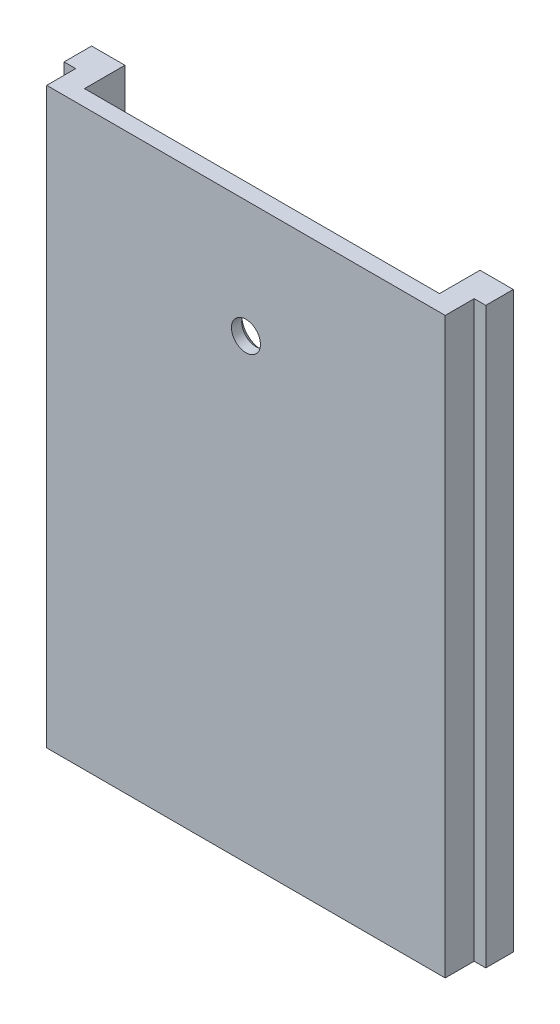
SolidWorks part; units mm, degrees
ref_plane "Alzado" through (0, 0, 0) normal (0, 0, 1) x (1, 0, 0)
ref_plane "Planta" through (0, 0, 0) normal (0, 1, 0) x (1, 0, 0)
ref_plane "Vista lateral" through (0, 0, 0) normal (1, 0, 0) x (0, 0, -1)
sketch "Croquis1" plane through (0, 0, 0) normal (0, 1, 0) x (1, 0, 0)
  line L5 (-4, 10) -> (-4, 19.5)
  line L14 (7.5, 19.5) -> (7.5, 5.5361)
  line L17 (-4, 19.5) -> (7.5, 19.5)
  line L19 (0, 0) -> (137.5, 0)
  line L20 (0, 0) -> (0, 10)
  line L21 (0, 10) -> (-4, 10)
  line L23 (7.5, 5.5361) -> (130, 5.5361)
  line L25 (68.75, 54.2093) -> (68.75, -41.2998) construction
  line L26 (137.5, 10) -> (141.5, 10)
  line L27 (137.5, 0) -> (137.5, 10)
  line L28 (141.5, 19.5) -> (130, 19.5)
  line L29 (130, 19.5) -> (130, 5.5361)
  line L30 (141.5, 10) -> (141.5, 19.5)
  point P3 (68.75, 5.5361)
  point P12 (68.75, 0)
  dimension "D1" = 68.75
  dimension "D2" = 10
  dimension "D3" = 9.5
  dimension "D4" = 11.5
  dimension "D5" = 72.75
  dimension "D7" = 5.5361
extrude "Saliente-Extruir4" add sketch "Croquis1" along normal blind 198 contours L17 L14 L23 L29 L28 L30 L26 L27 L19 L20 L21 L5
ref_plane "Plano1" through (68.75, 0, 0) normal (1, 0, 0) x (0, 0, -1)
sketch "Croquis2" plane through (0, 0, -5.5361) normal (0, 0, -1) x (-1, 0, 0)
  line L0 (-7.5, 0) -> (-130, 0) construction
  line L1 (-7.5, 0) -> (-130, 0) construction
  line L2 (-7.5, 198) -> (-7.5, 0) construction
  line L3 (-130, 198) -> (-130, 0) construction
  line L4 (-7.5, 198) -> (-7.5, 0) construction
  line L5 (-130, 198) -> (-130, 0) construction
  line L6 (-130, 108) -> (-7.5, 108)
  line L7 (-130, 105) -> (-7.5, 105)
  line L8 (-130, 108) -> (-130, 105)
  line L9 (-7.5, 108) -> (-7.5, 105)
  dimension "D1" = 108
  dimension "D2" = 3
extrude "Saliente-Extruir5" add sketch "Croquis2" along normal up to surface (13.9639 mm away) up to face at (135.75, 99, -19.5)
sketch "Croquis3" plane through (0, 0, 0) normal (0, 0, 1) x (1, 0, 0)
  line L0 (68.75, 198) -> (68.75, 0) construction
  line L1 (0, 198) -> (137.5, 198) construction
  line L2 (0, 0) -> (137.5, 0) construction
  circle A0 centre (68.75, 157.453) radius 5
  dimension "D1" = 10
extrude "Cortar-Extruir1" cut sketch "Croquis3" against normal blind 10
chamfer "Chaflán2" distance 2 angle 45 1 edges at (63.75, 157.453, -5.5361)
